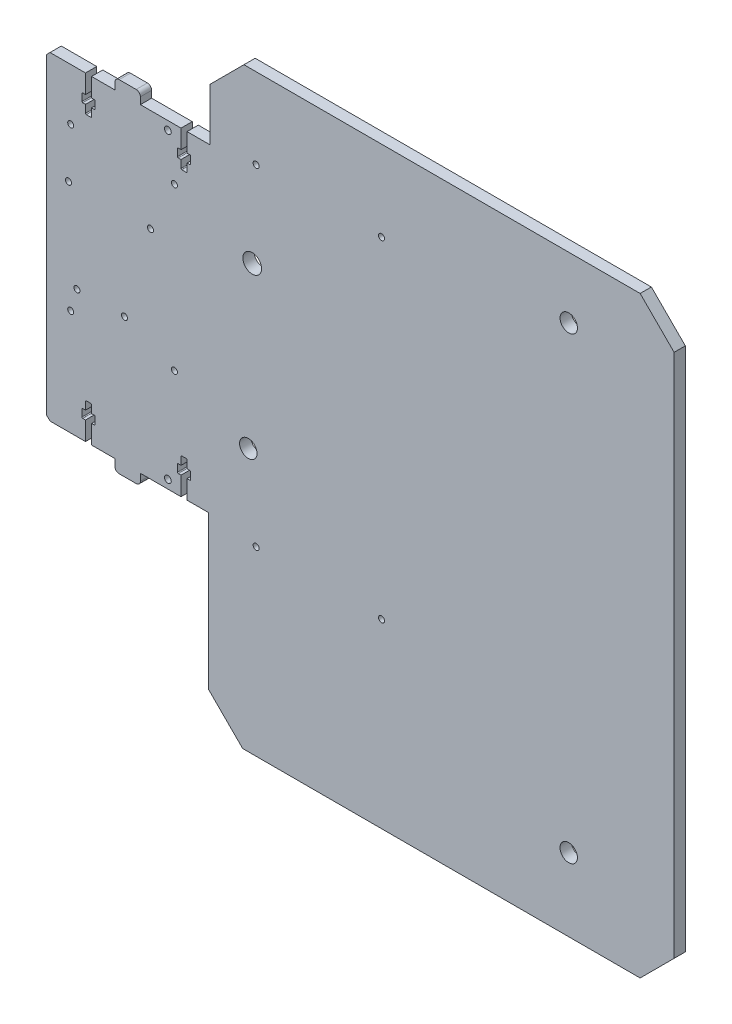
SolidWorks part; units mm, degrees
ref_plane "Front Plane" through (0, 0, 0) normal (0, 0, 1) x (1, 0, 0)
ref_plane "Top Plane" through (0, 0, 0) normal (0, 1, 0) x (1, 0, 0)
ref_plane "Right Plane" through (0, 0, 0) normal (1, 0, 0) x (0, 0, -1)
sketch "Model" plane through (0, 0, 0) normal (0, 0, 1) x (1, 0, 0)
  line L0 (40.15, 110.14) -> (40.15, 106.14)
  line L1 (26.41, 110.14) -> (40.15, 110.14)
  line L2 (26.41, 121.14) -> (26.41, 110.14)
  line L3 (27.995, 121.14) -> (26.41, 121.14)
  line L4 (28.495, 125.64) -> (28.495, 121.64)
  line L5 (26.41, 126.14) -> (27.995, 126.14)
  line L6 (26.41, 130.64) -> (26.41, 126.14)
  line L7 (23.36, 131.14) -> (25.91, 131.14)
  line L8 (22.86, 126.14) -> (22.86, 130.64)
  line L9 (21.275, 126.14) -> (22.86, 126.14)
  line L10 (20.775, 121.64) -> (20.775, 125.64)
  line L11 (22.86, 121.14) -> (21.275, 121.14)
  line L12 (22.86, 110.14) -> (22.86, 121.14)
  line L13 (2, 110.14) -> (22.86, 110.14)
  line L14 (0, 112.14) -> (2, 110.14)
  line L15 (0, 295.92) -> (0, 112.14)
  line L16 (2, 297.92) -> (0, 295.92)
  line L17 (22.86, 297.92) -> (2, 297.92)
  line L18 (22.86, 286.92) -> (22.86, 297.92)
  line L19 (21.275, 286.92) -> (22.86, 286.92)
  line L20 (20.775, 282.42) -> (20.775, 286.42)
  line L21 (22.86, 281.92) -> (21.275, 281.92)
  line L22 (22.86, 277.42) -> (22.86, 281.92)
  line L23 (25.91, 276.92) -> (23.36, 276.92)
  line L24 (26.41, 281.92) -> (26.41, 277.42)
  line L25 (27.995, 281.92) -> (26.41, 281.92)
  line L26 (28.495, 286.42) -> (28.495, 282.42)
  line L27 (26.41, 286.92) -> (27.995, 286.92)
  line L28 (26.41, 297.92) -> (26.41, 286.92)
  line L29 (40.15, 301.92) -> (40.15, 297.92)
  line L30 (52.65, 304.42) -> (42.65, 304.42)
  line L31 (55.15, 297.92) -> (55.15, 301.92)
  line L32 (79.05, 297.92) -> (55.15, 297.92)
  line L33 (79.05, 286.92) -> (79.05, 297.92)
  line L34 (77.465, 286.92) -> (79.05, 286.92)
  line L35 (76.965, 282.42) -> (76.965, 286.42)
  line L36 (79.05, 281.92) -> (77.465, 281.92)
  line L37 (79.05, 277.42) -> (79.05, 281.92)
  line L38 (82.1, 276.92) -> (79.55, 276.92)
  line L39 (82.6, 281.92) -> (82.6, 277.42)
  line L40 (84.185, 281.92) -> (82.6, 281.92)
  line L41 (84.685, 286.42) -> (84.685, 282.42)
  line L42 (82.6, 286.92) -> (84.185, 286.92)
  line L43 (82.6, 297.92) -> (82.6, 286.92)
  line L44 (96.05, 297.92) -> (82.6, 297.92)
  line L45 (96.05, 328.72) -> (96.05, 297.92)
  line L46 (116.05, 348.72) -> (96.05, 328.72)
  line L47 (349.1, 348.72) -> (116.05, 348.72)
  line L48 (369.1, 328.72) -> (349.1, 348.72)
  line L49 (369.1, 20) -> (369.1, 328.72)
  line L50 (349.1, 0) -> (369.1, 20)
  line L51 (115.3, 0) -> (349.1, 0)
  line L52 (95.3, 20) -> (115.3, 0)
  line L53 (95.3, 110.14) -> (95.3, 20)
  line L54 (82.6, 110.14) -> (95.3, 110.14)
  line L55 (82.6, 121.14) -> (82.6, 110.14)
  line L56 (84.185, 121.14) -> (82.6, 121.14)
  line L57 (84.685, 125.64) -> (84.685, 121.64)
  line L58 (82.6, 126.14) -> (84.185, 126.14)
  line L59 (82.6, 130.64) -> (82.6, 126.14)
  line L60 (79.55, 131.14) -> (82.1, 131.14)
  line L61 (79.05, 126.14) -> (79.05, 130.64)
  line L62 (77.465, 126.14) -> (79.05, 126.14)
  line L63 (76.965, 121.64) -> (76.965, 125.64)
  line L64 (79.05, 121.14) -> (77.465, 121.14)
  line L65 (79.05, 110.14) -> (79.05, 121.14)
  line L66 (55.15, 110.14) -> (79.05, 110.14)
  line L67 (55.15, 106.14) -> (55.15, 110.14)
  line L68 (42.65, 103.64) -> (52.65, 103.64)
  line L69 (40.15, 297.92) -> (26.41, 297.92)
  circle A0 centre (123.225, 301.35) radius 1.775
  circle A1 centre (196.975, 301.35) radius 1.775
  circle A2 centre (123.225, 106.69) radius 1.775
  circle A3 centre (196.975, 106.69) radius 1.775
  circle A4 centre (120.9248, 249.972) radius 5.5
  circle A5 centre (17.84, 185.23) radius 1.775
  circle A6 centre (45.79, 185.23) radius 1.775
  circle A7 centre (61.09, 237.62) radius 1.775
  circle A8 centre (12.84, 237.62) radius 1.775
  circle A9 centre (14.175, 172.42) radius 1.775
  circle A10 centre (75.175, 172.42) radius 1.775
  circle A11 centre (14.175, 267.42) radius 1.775
  circle A12 centre (75.175, 267.42) radius 1.775
  circle A13 centre (71.3, 292.92) radius 2
  circle A14 centre (71.3, 115.14) radius 2
  circle A15 centre (307.1, 312.72) radius 5.125
  circle A16 centre (118.6291, 154.5256) radius 5.125
  circle A17 centre (307.1, 42.845) radius 5.125
  arc A18 (40.15, 106.14) -> (42.65, 103.64) centre (42.65, 106.14) ccw
  arc A19 (27.995, 121.14) -> (28.495, 121.64) centre (27.995, 121.64) ccw
  arc A20 (28.495, 125.64) -> (27.995, 126.14) centre (27.995, 125.64) ccw
  arc A21 (26.41, 130.64) -> (25.91, 131.14) centre (25.91, 130.64) ccw
  arc A22 (23.36, 131.14) -> (22.86, 130.64) centre (23.36, 130.64) ccw
  arc A23 (21.275, 126.14) -> (20.775, 125.64) centre (21.275, 125.64) ccw
  arc A24 (20.775, 121.64) -> (21.275, 121.14) centre (21.275, 121.64) ccw
  arc A25 (21.275, 286.92) -> (20.775, 286.42) centre (21.275, 286.42) ccw
  arc A26 (20.775, 282.42) -> (21.275, 281.92) centre (21.275, 282.42) ccw
  arc A27 (22.86, 277.42) -> (23.36, 276.92) centre (23.36, 277.42) ccw
  arc A28 (25.91, 276.92) -> (26.41, 277.42) centre (25.91, 277.42) ccw
  arc A29 (27.995, 281.92) -> (28.495, 282.42) centre (27.995, 282.42) ccw
  arc A30 (28.495, 286.42) -> (27.995, 286.92) centre (27.995, 286.42) ccw
  arc A31 (42.65, 304.42) -> (40.15, 301.92) centre (42.65, 301.92) ccw
  arc A32 (55.15, 301.92) -> (52.65, 304.42) centre (52.65, 301.92) ccw
  arc A33 (77.465, 286.92) -> (76.965, 286.42) centre (77.465, 286.42) ccw
  arc A34 (76.965, 282.42) -> (77.465, 281.92) centre (77.465, 282.42) ccw
  arc A35 (79.05, 277.42) -> (79.55, 276.92) centre (79.55, 277.42) ccw
  arc A36 (82.1, 276.92) -> (82.6, 277.42) centre (82.1, 277.42) ccw
  arc A37 (84.185, 281.92) -> (84.685, 282.42) centre (84.185, 282.42) ccw
  arc A38 (84.685, 286.42) -> (84.185, 286.92) centre (84.185, 286.42) ccw
  arc A39 (84.185, 121.14) -> (84.685, 121.64) centre (84.185, 121.64) ccw
  arc A40 (84.685, 125.64) -> (84.185, 126.14) centre (84.185, 125.64) ccw
  arc A41 (82.6, 130.64) -> (82.1, 131.14) centre (82.1, 130.64) ccw
  arc A42 (79.55, 131.14) -> (79.05, 130.64) centre (79.55, 130.64) ccw
  arc A43 (77.465, 126.14) -> (76.965, 125.64) centre (77.465, 125.64) ccw
  arc A44 (76.965, 121.64) -> (77.465, 121.14) centre (77.465, 121.64) ccw
  arc A45 (52.65, 103.64) -> (55.15, 106.14) centre (52.65, 106.14) ccw
extrude "Boss-Extrude1" add sketch "Model" along normal blind 6.6
